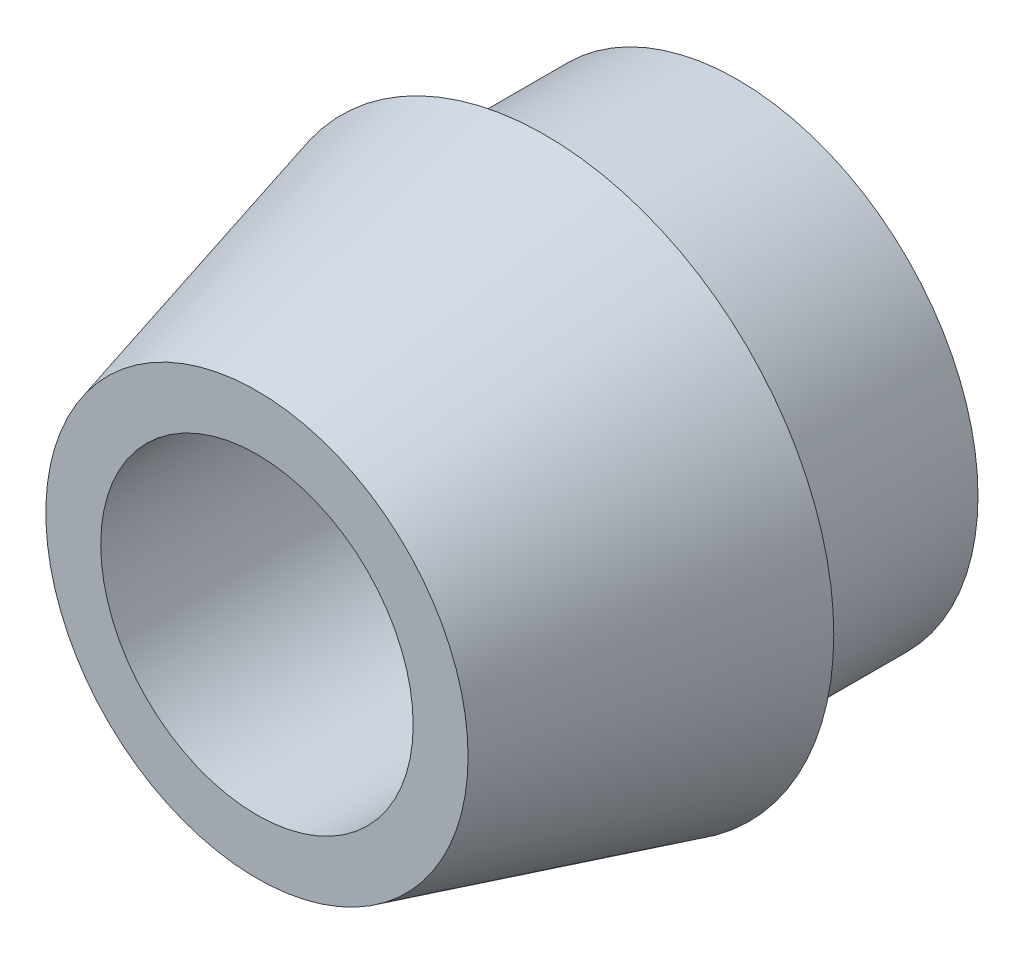
SolidWorks part; units mm, degrees
ref_plane "Front Plane" through (0, 0, 0) normal (0, 0, 1) x (1, 0, 0)
ref_plane "Top Plane" through (0, 0, 0) normal (0, 1, 0) x (1, 0, 0)
ref_plane "Right Plane" through (0, 0, 0) normal (1, 0, 0) x (0, 0, -1)
sketch "Sketch3" plane through (0, 0, 0) normal (0, 0, 1) x (1, 0, 0)
  circle A0 centre (0, 0) radius 50
  circle A1 centre (0, 0) radius 35
  dimension "D1" = 100
  dimension "D2" = 70
extrude "Boss-Extrude3" add sketch "Sketch3" along normal blind 40
sketch "Sketch6" plane through (0, 0, 40) normal (0, 0, 1) x (1, 0, 0)
  circle A0 centre (0, 0) radius 60
  dimension "D1" = 120
extrude "Boss-Extrude5" add sketch "Sketch6" along normal blind 60 draft 15
sketch "Sketch7" plane through (0, 0, 100) normal (0, 0, 1) x (1, 0, 0)
  circle A0 centre (0, 0) radius 32.5
  dimension "D1" = 65
extrude "Cut-Extrude1" cut sketch "Sketch7" against normal through all
